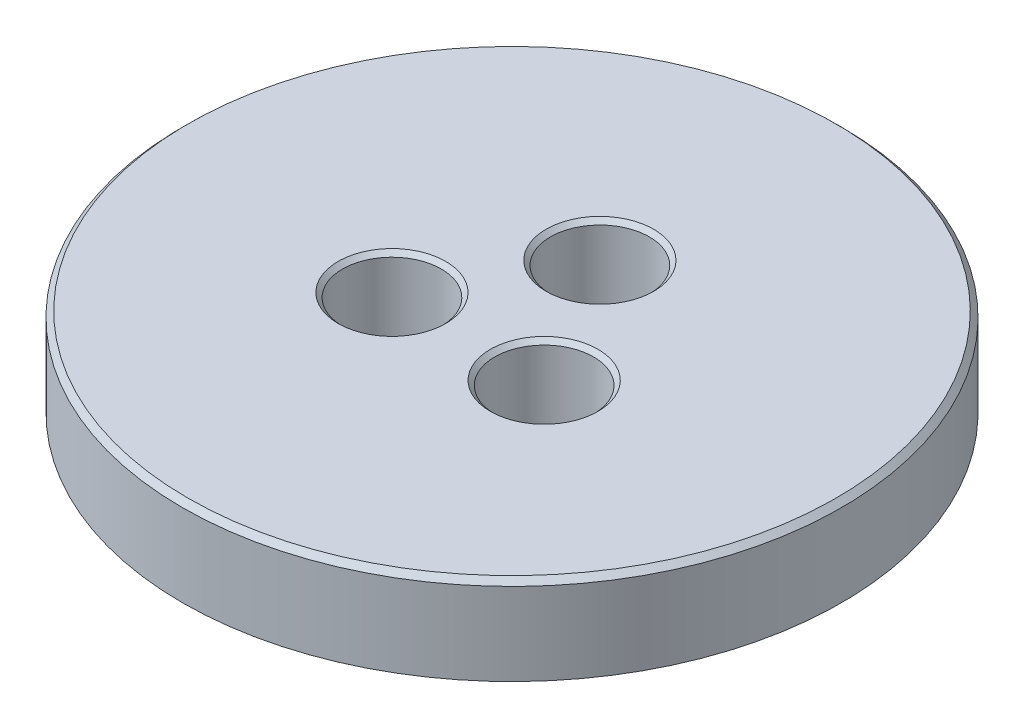
SolidWorks part; units mm, degrees
ref_plane "Front Plane" through (0, 0, 0) normal (0, 0, 1) x (1, 0, 0)
ref_plane "Top Plane" through (0, 0, 0) normal (0, 1, 0) x (1, 0, 0)
ref_plane "Right Plane" through (0, 0, 0) normal (1, 0, 0) x (0, 0, -1)
sketch "Sketch1" plane through (0, 0, 0) normal (0, 0, 1) x (1, 0, 0)
  line L12 (0, 0) -> (7.5, 0)
  line L13 (0, 0) -> (0, 2)
  line L15 (7.5, 0) -> (7.5, 2)
  line L16 (0, 2) -> (7.5, 2)
  point P12 (0, 2)
  dimension "D1" = 7.5
  dimension "D2" = 2
revolve "Revolve1" add sketch "Sketch1" angle 360 about L13
sketch "Sketch2" plane through (0, 0, 0) normal (0, 1, 0) x (1, 0, 0)
  line L0 (3.9222, 4.9819) -> (3.3067, -0.1371) construction
  line L2 (0, 0) -> (-3.56, -5.6523) construction
  line L4 (0, 0) -> (3.56, -5.6523) construction
  line L6 (3.8069, 4.0233) -> (3.5375, 1.7822) construction
  line L7 (3.8069, 4.0233) -> (6.048, 3.7538) construction
  line L8 (3.5375, 1.7822) -> (5.7785, 1.5128) construction
  line L9 (6.048, 3.7538) -> (5.7785, 1.5128) construction
  line L10 (3.6385, 2.6226) -> (5.8796, 2.3532) construction
  line L12 (4.658, 1.6475) -> (4.9275, 3.8885) construction
  line L14 (4.759, 2.4879) -> (4.8762, 3.4624)
  line L15 (4.759, 2.4879) -> (5.8796, 2.3532) construction
  line L16 (4.759, 2.4879) -> (4.8943, 3.6127) construction
  line L17 (5.8796, 2.3532) -> (6.0148, 3.4779) construction
  line L18 (4.8943, 3.6127) -> (6.0148, 3.4779) construction
  line L19 (4.759, 2.4879) -> (6.0148, 3.4779) construction
  line L20 (5.8796, 2.3532) -> (4.8943, 3.6127) construction
  line L21 (4.9875, 3.4935) -> (5.3483, 3.0323)
  line L22 (5.4362, 3.0217) -> (5.896, 3.3843)
  line L23 (5.9967, 3.3277) -> (5.8796, 2.3532)
  line L24 (0, 2) -> (0, 0) construction
  line L25 (0, 0) -> (-1.7321, -1) construction
  line L26 (1.7321, -1) -> (0, 0) construction
  circle A5 centre (0, 0) radius 7.125 construction
  circle A6 centre (0, 3.8183) radius 3.3067
  circle A7 centre (3.3067, -1.9091) radius 3.3067
  circle A8 centre (-3.3067, -1.9091) radius 3.3067
  circle A9 centre (-4.7882, 2.7645) radius 1.5961
  circle A10 centre (4.7882, 2.7645) radius 1.5961
  circle A11 centre (0, -5.5289) radius 1.5961
  circle A12 centre (-2.3533, -5.8877) radius 0.7844
  circle A13 centre (2.3533, -5.8877) radius 0.7844
  circle A14 centre (6.2755, 0.9058) radius 0.7844
  circle A15 centre (3.9222, 4.9819) radius 0.7844
  circle A16 centre (-6.2755, 0.9058) radius 0.7844
  circle A17 centre (-3.9222, 4.9819) radius 0.7844
  circle A18 centre (0, 0) radius 0.5116
  circle A19 centre (-3.0733, 1.7744) radius 0.3842
  circle A20 centre (0, -3.5487) radius 0.3842
  circle A21 centre (3.0733, 1.7744) radius 0.3842
  circle A22 centre (-6.6751, -0.2569) radius 0.445
  circle A23 centre (-3.115, 5.9092) radius 0.445
  circle A24 centre (3.115, 5.9092) radius 0.445
  circle A25 centre (6.6751, -0.2569) radius 0.445
  circle A26 centre (3.56, -5.6523) radius 0.445
  circle A27 centre (-3.56, -5.6523) radius 0.445
  circle A32 centre (-3.3067, -0.1371) radius 1.5347 construction
  circle A33 centre (-4.8414, -2.7952) radius 1.5347 construction
  circle A34 centre (-1.7721, -2.7952) radius 1.5347 construction
  circle A35 centre (-1.7321, -1) radius 1.125
  circle A36 centre (0, 5.5903) radius 1.5347 construction
  circle A37 centre (1.5347, 2.9322) radius 1.5347 construction
  circle A38 centre (-1.5347, 2.9322) radius 1.5347 construction
  circle A39 centre (3.3067, -0.1371) radius 1.5347 construction
  circle A40 centre (4.8414, -2.7952) radius 1.5347 construction
  circle A41 centre (1.7721, -2.7952) radius 1.5347 construction
  circle A42 centre (1.7321, -1) radius 1.125
  circle A43 centre (0, 2) radius 1.125
  circle A50 centre (-4.2329, -5.3765) radius 0.2822
  circle A51 centre (-6.7726, -0.9775) radius 0.2822
  circle A52 centre (-2.5397, 6.354) radius 0.2822
  circle A53 centre (2.5397, 6.354) radius 0.2822
  circle A54 centre (6.7726, -0.9775) radius 0.2822
  circle A55 centre (4.2329, -5.3765) radius 0.2822
  circle A129 centre (0.6228, 0.3596) radius 0.2076
  circle A130 centre (-4.9696, 4.6625) radius 0.3106
  circle A131 centre (-6.5226, 1.9726) radius 0.3106
  circle A132 centre (-5.2772, 1.0156) radius 0.2199
  circle A133 centre (-3.5181, 4.0624) radius 0.2199
  circle A134 centre (-1.553, -6.6351) radius 0.3106
  circle A135 centre (1.553, -6.6351) radius 0.3106
  circle A136 centre (1.7591, -5.078) radius 0.2199
  circle A137 centre (-1.7591, -5.078) radius 0.2199
  circle A138 centre (6.5226, 1.9726) radius 0.3106
  circle A139 centre (5.2772, 1.0156) radius 0.2199
  circle A140 centre (3.5181, 4.0624) radius 0.2199
  circle A141 centre (4.9696, 4.6625) radius 0.3106
  circle A142 centre (-6.7773, -1.4534) radius 0.1936
  circle A143 centre (-2.13, 6.596) radius 0.1936
  circle A144 centre (2.13, 6.596) radius 0.1936
  circle A145 centre (6.7773, -1.4534) radius 0.1936
  circle A146 centre (4.6473, -5.1426) radius 0.1936
  circle A147 centre (-4.6473, -5.1426) radius 0.1936
  circle A148 centre (-0.6228, 0.3596) radius 0.2076
  circle A149 centre (0, -0.7192) radius 0.2076
  circle A150 centre (-3.1057, 2.3054) radius 0.1479
  circle A151 centre (-2.591, 1.4959) radius 0.1727
  circle A152 centre (-3.5494, 1.5369) radius 0.1479
  circle A153 centre (-6.5182, 2.4461) radius 0.163
  circle A154 centre (-6.8057, 1.6432) radius 0.1237
  circle A155 centre (-6.1644, 1.7795) radius 0.0963
  circle A156 centre (-6.9651, 0.2681) radius 0.1548
  circle A157 centre (-6.1624, 0) radius 0.1284
  circle A158 centre (-5.3775, 4.4218) radius 0.163
  circle A159 centre (-4.8259, 5.0723) radius 0.1237
  circle A160 centre (-4.6233, 4.4488) radius 0.0963
  circle A161 centre (-3.7147, 5.8979) radius 0.1548
  circle A162 centre (-3.0812, 5.3368) radius 0.1284
  circle A163 centre (-1.8286, 6.7407) radius 0.1407
  circle A164 centre (-6.7519, -1.7867) radius 0.1407
  circle A165 centre (1.8286, 6.7407) radius 0.1407
  circle A166 centre (3.7147, 5.8979) radius 0.1548
  circle A167 centre (3.0812, 5.3368) radius 0.1284
  circle A168 centre (5.3775, 4.4218) radius 0.163
  circle A169 centre (4.8259, 5.0723) radius 0.1237
  circle A170 centre (4.6233, 4.4488) radius 0.0963
  circle A171 centre (3.1057, 2.3054) radius 0.1479
  circle A172 centre (3.5494, 1.5369) radius 0.1479
  circle A173 centre (2.591, 1.4959) radius 0.1727
  circle A174 centre (6.5182, 2.4461) radius 0.163
  circle A175 centre (6.8057, 1.6432) radius 0.1237
  circle A176 centre (6.9651, 0.2681) radius 0.1548
  circle A177 centre (6.1624, 0) radius 0.1284
  circle A178 centre (6.7519, -1.7867) radius 0.1407
  circle A179 centre (0, -2.9918) radius 0.1727
  circle A180 centre (0.4437, -3.8424) radius 0.1479
  circle A181 centre (-0.4437, -3.8424) radius 0.1479
  circle A182 centre (-4.9233, -4.954) radius 0.1407
  circle A183 centre (4.9233, -4.954) radius 0.1407
  circle A184 centre (1.1407, -6.868) radius 0.163
  circle A185 centre (1.9798, -6.7155) radius 0.1237
  circle A186 centre (-1.1407, -6.868) radius 0.163
  circle A187 centre (-1.9798, -6.7155) radius 0.1237
  circle A188 centre (-3.2504, -6.166) radius 0.1548
  circle A189 centre (3.2504, -6.166) radius 0.1548
  circle A190 centre (3.0812, -5.3368) radius 0.1284
  circle A191 centre (-3.0812, -5.3368) radius 0.1284
  arc A192 (3.6385, 2.6226) -> (4.759, 2.4879) centre (4.1988, 2.5552) ccw
  arc A193 (5.896, 3.3843) -> (5.9967, 3.3277) centre (5.9347, 3.3352) cw
  arc A194 (5.3483, 3.0323) -> (5.4362, 3.0217) centre (5.3975, 3.0708) ccw
  arc A195 (4.9875, 3.4935) -> (4.8762, 3.4624) centre (4.9383, 3.455) ccw
  point P0 (0, 0)
  point P189 (5.3869, 2.9829)
  point P193 (5.3869, 2.9829)
  point P196 (4.8943, 3.6127)
  dimension "D4" = 1.1286
  dimension "D6" = 0.0625
  dimension "D1" = 14.25
  dimension "D7" = 2.25
  dimension "D8" = 2.25
  dimension "D9" = 2.25
  dimension "D2" = 2.2572
  dimension "D3" = 1.4107
  dimension "D5" = 1.1329
  dimension "D10" = 120
  dimension "D11" = 120
  dimension "D12" = 2
  dimension "D13" = 2
  dimension "D14" = 2
extrude "Cut-Extrude1" cut sketch "Sketch2" along normal through all contours A43 | A35 | A42
chamfer "Chamfer1" [suppressed] distance 0.5 angle 45
chamfer "Chamfer2" distance 0.1 angle 45 3 edges at (1.7321, 2, 2.125) (-1.7321, 2, 2.125) (0, 2, -0.875)
chamfer "Chamfer3" distance 0.125 angle 45 1 edges at (0, 2, -7.5)
equation "\"D\"= \"B\" - 0.75'design diameter"
equation "\"B\"= 15mm'button diameter"
equation "\"h\"= 0.099 * \"D\"'offset of JM from of box"
equation "\"w\"= 0.0795 * \"D\"'width of J"
equation "\"D1@Sketch2\"= \"D\""
equation "\"D3@Sketch2\"=\"h\""
equation "\"D5@Sketch2\"=\"w\""
equation "\"D1@Sketch1\"=\"B\"/2"
